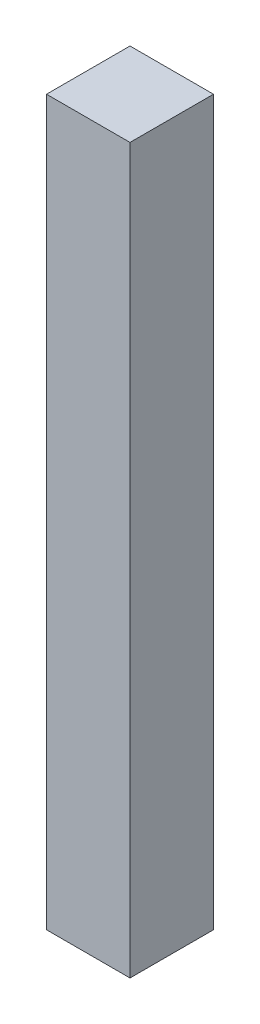
SolidWorks part; units mm, degrees
ref_plane "Front Plane" through (0, 0, 0) normal (0, 0, 1) x (1, 0, 0)
ref_plane "Top Plane" through (0, 0, 0) normal (0, 1, 0) x (1, 0, 0)
ref_plane "Right Plane" through (0, 0, 0) normal (1, 0, 0) x (0, 0, -1)
sketch "Sketch1" plane through (0, 0, 0) normal (0, 1, 0) x (1, 0, 0)
  line L1 (-40.0482, 5.3675) -> (-10.0482, 5.3675)
  line L2 (-40.0482, 5.3675) -> (-40.0482, -24.6325)
  line L3 (-40.0482, -24.6325) -> (-10.0482, -24.6325)
  line L4 (-10.0482, 5.3675) -> (-10.0482, -24.6325)
  dimension "D1" = 30
  dimension "D2" = 30
extrude "Boss-Extrude1" add sketch "Sketch1" along normal blind 260
